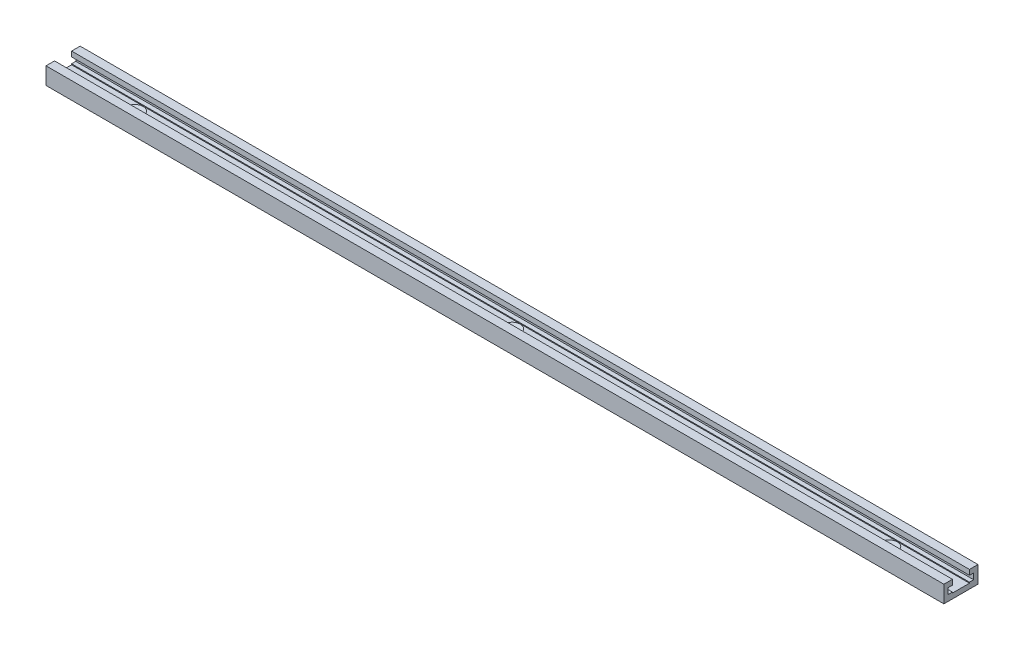
SolidWorks part; units mm, degrees
material "Aluminium"
ref_plane "Front Plane" through (0, 0, 0) normal (0, 0, 1) x (1, 0, 0)
ref_plane "Top Plane" through (0, 0, 0) normal (0, 1, 0) x (1, 0, 0)
ref_plane "Right Plane" through (0, 0, 0) normal (1, 0, 0) x (0, 0, -1)
sketch "Sketch1" plane through (0, 0, 0) normal (1, 0, 0) x (0, 0, -1)
  line L0 (-4.75, 4.75) -> (-9.5, 4.75)
  line L1 (9.5, -4.75) -> (-9.5, -4.75)
  line L2 (9.5, -4.75) -> (9.5, 4.75)
  line L3 (9.5, 4.75) -> (4.75, 4.75)
  line L4 (-9.5, -4.75) -> (-9.5, 4.75)
  line L5 (9.5, -4.75) -> (-9.5, 4.75) construction
  line L6 (9.5, 4.75) -> (-9.5, -4.75) construction
  line L8 (-4.75, 4.75) -> (-4.75, 1.9)
  line L9 (-4.75, -1.9) -> (4.75, -1.9)
  line L10 (4.75, 4.75) -> (4.75, 1.9)
  line L11 (-7.1, 1.9) -> (-4.75, 1.9)
  line L12 (-7.1, 1.9) -> (-7.1, -1.4)
  line L13 (-7.1, -1.4) -> (-4.75, -1.4)
  line L14 (7.1, 1.9) -> (7.1, -1.4)
  line L15 (4.75, 1.9) -> (7.1, 1.9)
  line L16 (4.75, -1.4) -> (7.1, -1.4)
  line L17 (-4.75, -1.4) -> (-4.75, -1.9)
  line L18 (4.75, -1.4) -> (4.75, -1.9)
  line L19 (-4.75, 4.75) -> (4.75, 4.75) construction
  line L20 (0, 4.75) -> (0, 0) construction
  line L21 (0, -1.9) -> (0, -4.75) construction
  line L22 (-7.1, 0.25) -> (7.1, 0.25) construction
  point P0 (0, 0)
  point P14 (4.75, 3.325)
  point P25 (0, 0.25)
  dimension "D1" = 19
  dimension "D2" = 9.5
  dimension "D3" = 3.3
  dimension "D4" = 9.5
  dimension "D5" = 0.5
  dimension "D6" = 14.2
extrude "Boss-Extrude1" add sketch "Sketch1" along normal mid plane 500
hole_wizard "CSK for M4 Hex Socket Countersunk Head Screw1" positions "Sketch2" profile "Sketch3" countersink size "M4" standard "DIN"
sketch "Sketch2" plane through (0, -1.9, 0) normal (0, 1, 0) x (1, 0, 0)
  line L0 (-210, 0) -> (0, 0) construction
  line L1 (0, 0) -> (210, 0) construction
  point P0 (0, 0)
  point P3 (-210, 0)
  point P5 (210, 0)
  dimension "D1" = 210
sketch "Sketch3" plane through (0, -1.9, 0) normal (1, 0, 0) x (0, 0, 1)
  line L0 (0, 0) -> (0, 6.7519)
  line L1 (0, 6.7519) -> (2.25, 5.4)
  line L2 (2.25, 5.4) -> (2.25, 2.34)
  line L3 (2.25, 2.34) -> (4.59, 0)
  line L5 (4.59, 0) -> (0, 0)
  line L6 (-2.25, 2.34) -> (-4.59, 0) construction
  line L10 (0, 6.7519) -> (-2.25, 5.4) construction
  line L11 (0, -6.35) -> (0, 107.95) construction
  dimension "Hole Dia." = 4.5
  dimension "Hole Depth" = 5.4
  dimension "Near C'Sink Dia." = 9.18
  dimension "Near C'Sink Angle" = 90
  dimension "Drill Angle" = 118
